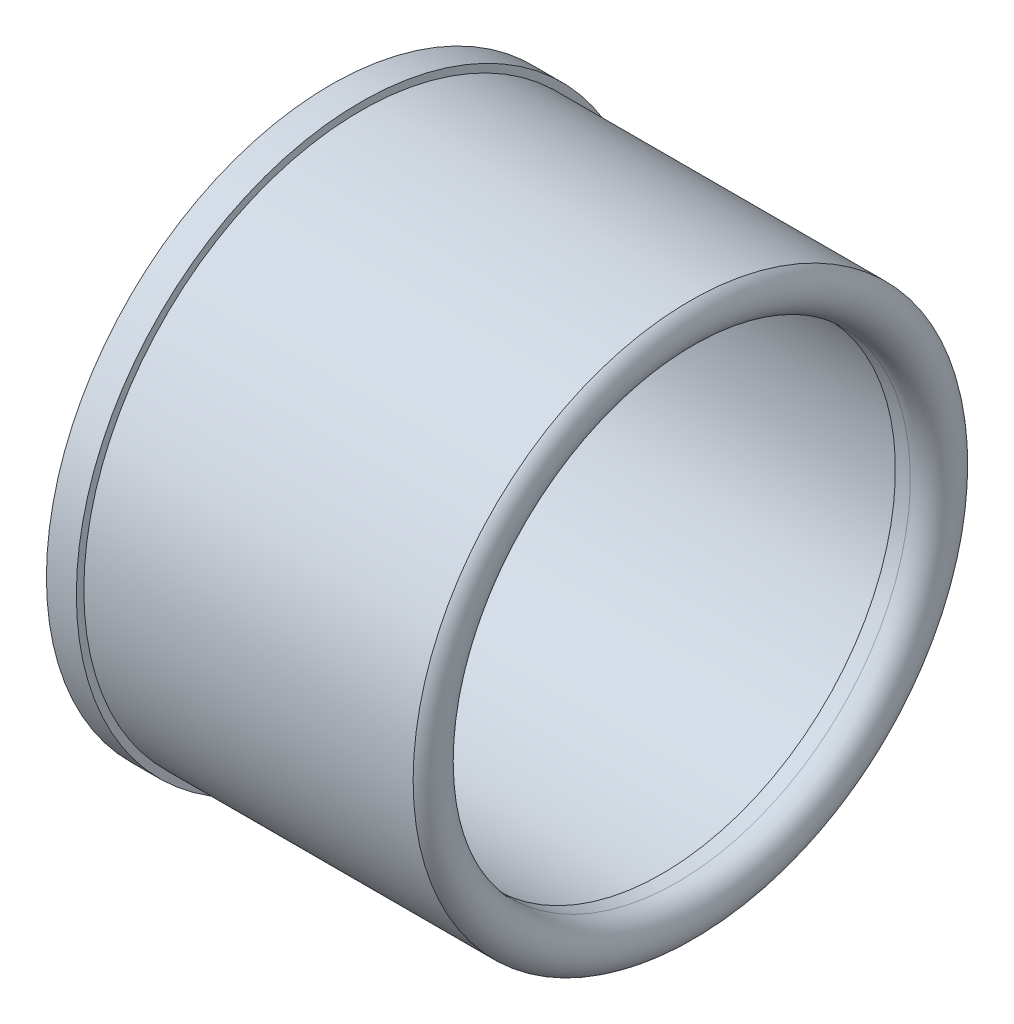
SolidWorks part; units mm, degrees
ref_plane "Front Plane" through (0, 0, 0) normal (0, 0, 1) x (1, 0, 0)
ref_plane "Top Plane" through (0, 0, 0) normal (0, 1, 0) x (1, 0, 0)
ref_plane "Right Plane" through (0, 0, 0) normal (1, 0, 0) x (0, 0, -1)
ref_plane "Plane1" through (0, 0, 0) normal (0, 0, -1) x (-1, 0, 0)
sketch "Sketch1" plane through (0, 0, 0) normal (0, 0, -1) x (-1, 0, 0)
  line L0 (-11.9728, -0.7333) -> (-11.9728, -0.4833)
  line L1 (-11.9728, -0.4833) -> (-0.9121, -0.4833)
  line L2 (-0.9121, -0.4833) -> (-0.9121, 0.9667)
  line L3 (-0.9121, 0.9667) -> (-1.9121, 0.9667)
  line L4 (-1.9121, 0.9667) -> (-1.9121, 0.7167)
  line L5 (-1.9121, 0.7167) -> (-12.9121, 0.7167)
  line L6 (-12.4728, -0.7333) -> (-11.9728, -0.7333)
  line L7 (-12.1757, -8.5333) -> (0.2029, -8.5333) construction
  arc A0 (-12.9121, 0.7167) -> (-12.4728, -0.7333) centre (-12.4728, 0.0583) ccw
  dimension "D1" = 11
  dimension "D2" = 1.45
  dimension "D3" = 0.25
  dimension "D4" = 0.25
  dimension "D5" = 16.1
  dimension "D6" = 1
  dimension "D7" = 0.5
revolve "Revolve1" add sketch "Sketch1" angle 360 about L7
